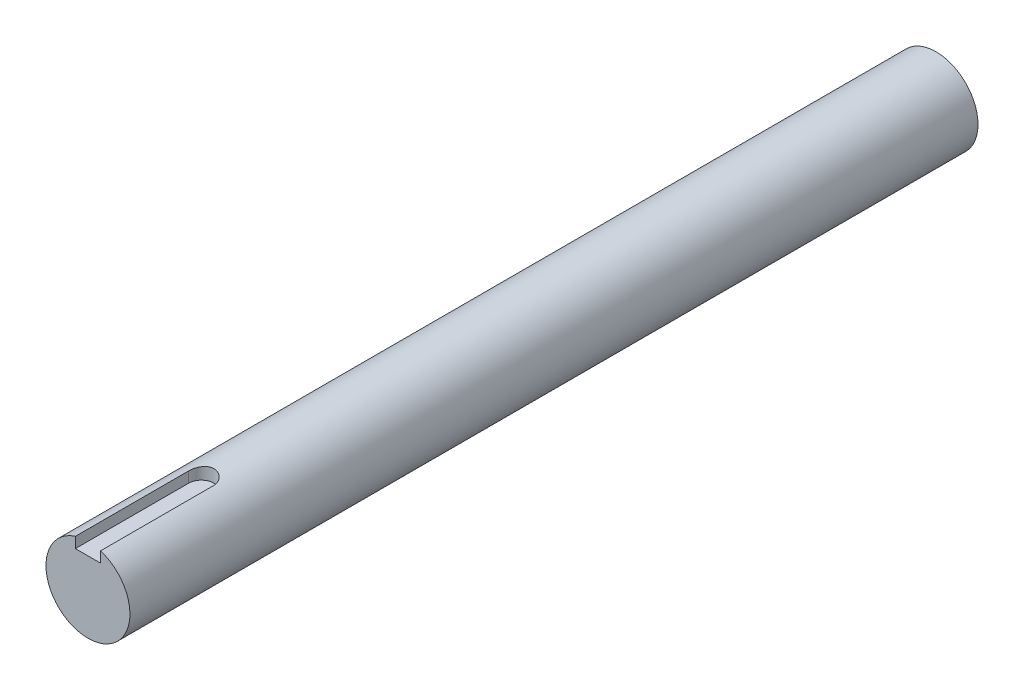
SolidWorks part; units mm, degrees
material "201 Annealed Stainless Steel (SS)"
ref_plane "Front Plane" through (0, 0, 0) normal (0, 0, 1) x (1, 0, 0)
ref_plane "Top Plane" through (0, 0, 0) normal (0, 1, 0) x (1, 0, 0)
ref_plane "Right Plane" through (0, 0, 0) normal (1, 0, 0) x (0, 0, -1)
sketch "Sketch1" plane through (0, 0, 0) normal (0, 0, 1) x (1, 0, 0)
  circle A0 centre (0, 0) radius 5
  dimension "D1" = 10
extrude "Boss-Extrude1" add sketch "Sketch1" along normal mid plane 101 contours A0
sketch "Sketch2" plane through (0, 0, 0) normal (0, 1, 0) x (1, 0, 0)
  line L0 (0, 0) -> (0, -50000) construction
  line L1 (-5, -50.5) -> (5, -50.5) construction
  line L3 (-1.5, -37) -> (-1.5, -50.5)
  line L4 (-1.5, -50.5) -> (1.5, -50.5)
  line L5 (1.5, -37) -> (1.5, -50.5)
  line L6 (-1.5, -37) -> (1.5, -50.5) construction
  line L7 (-1.5, -50.5) -> (1.5, -37) construction
  arc A0 (-1.5, -37) -> (1.5, -37) centre (0, -37) cw
  point P3 (0, -43.75)
  point P11 (0, -35.5)
  dimension "D1" = 3
  dimension "D2" = 15
extrude "Cut-Extrude1" cut sketch "Sketch2" against normal blind 1.5 from offset 5
